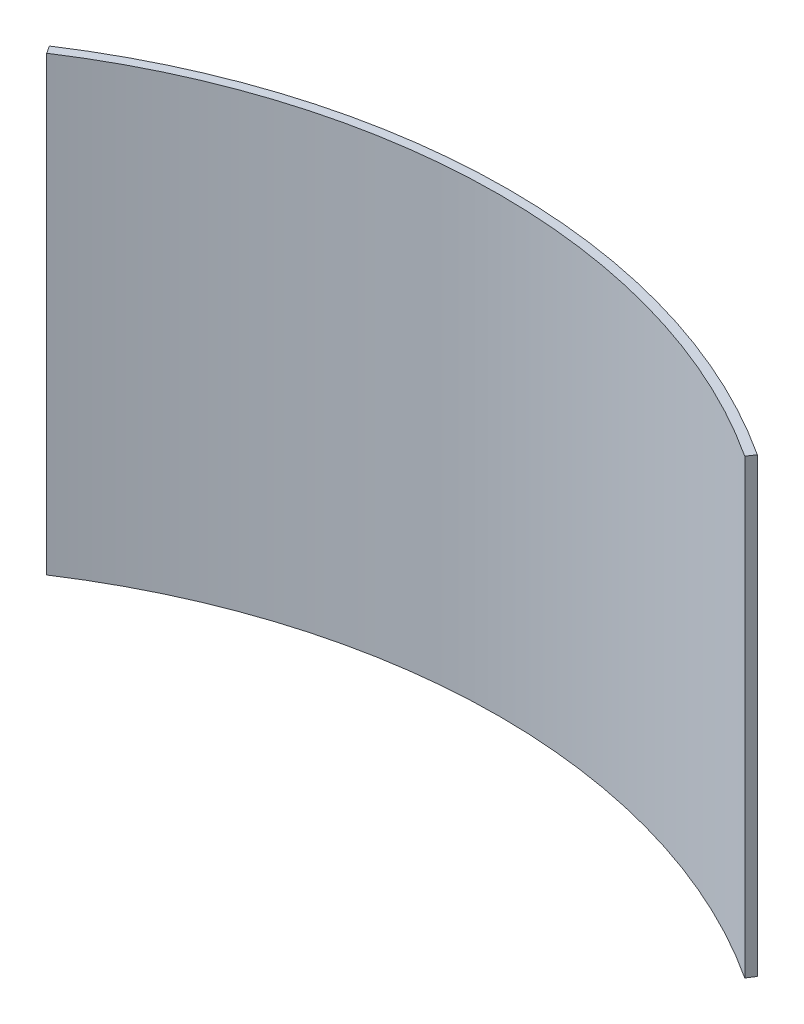
SolidWorks part; units mm, degrees
ref_plane "Спереди" through (0, 0, 0) normal (0, 0, 1) x (1, 0, 0)
ref_plane "Сверху" through (0, 0, 0) normal (0, 1, 0) x (1, 0, 0)
ref_plane "Справа" through (0, 0, 0) normal (1, 0, 0) x (0, 0, -1)
sketch "Эскиз1" plane through (0, 0, 0) normal (0, 1, 0) x (1, 0, 0)
  line L0 (0, 57.5) -> (223.2588, 57.5) construction
  line L1 (92.5, 92.5) -> (236.2741, 92.5) construction
  arc A0 (14.6418, 57.5) -> (249.6418, 57.5) centre (132.1418, -122.2321) cw
  dimension "D1" = 35
  dimension "D2" = 235
extrude "Вытянуть-Тонкостенный1" add sketch "Эскиз1" along normal blind 150 thin
